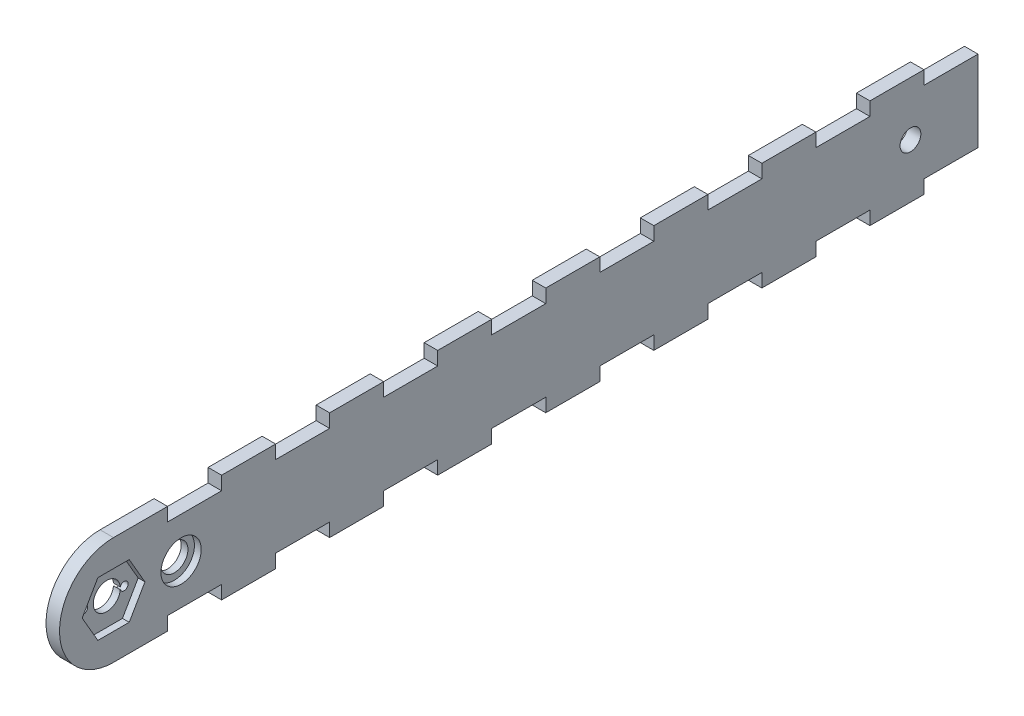
SolidWorks part; units mm, degrees
ref_plane "Front Plane" through (0, 0, 0) normal (0, 0, 1) x (1, 0, 0)
ref_plane "Top Plane" through (0, 0, 0) normal (0, 1, 0) x (1, 0, 0)
ref_plane "Right Plane" through (0, 0, 0) normal (1, 0, 0) x (0, 0, -1)
sketch "Sketch1" plane through (0, 0, 0) normal (1, 0, 0) x (0, 0, -1)
  line L0 (0, 12.7) -> (203.2, 12.7)
  line L1 (0, -12.7) -> (203.2, -12.7)
  line L2 (203.2, -12.7) -> (203.2, 12.7)
  line L3 (203.2, 0) -> (7.9375, 0) construction
  line L4 (203.2, 12.7) -> (190.5, 12.7)
  line L5 (203.2, 12.7) -> (203.2, 9.525)
  line L6 (203.2, 9.525) -> (190.5, 9.525)
  line L7 (190.5, 12.7) -> (190.5, 9.525)
  line L8 (190.5, -12.7) -> (190.5, -9.525)
  line L9 (203.2, -9.525) -> (190.5, -9.525)
  line L10 (203.2, -12.7) -> (203.2, -9.525)
  line L11 (165.1, 12.7) -> (165.1, 9.525)
  line L12 (165.1, -12.7) -> (165.1, -9.525)
  line L13 (177.8, -9.525) -> (165.1, -9.525)
  line L14 (177.8, 9.525) -> (165.1, 9.525)
  line L15 (177.8, 12.7) -> (177.8, 9.525)
  line L16 (177.8, -12.7) -> (177.8, -9.525)
  line L17 (139.7, 12.7) -> (139.7, 9.525)
  line L18 (139.7, -12.7) -> (139.7, -9.525)
  line L19 (152.4, -9.525) -> (139.7, -9.525)
  line L20 (152.4, 9.525) -> (139.7, 9.525)
  line L21 (152.4, 12.7) -> (152.4, 9.525)
  line L22 (152.4, -12.7) -> (152.4, -9.525)
  line L23 (114.3, 12.7) -> (114.3, 9.525)
  line L24 (114.3, -12.7) -> (114.3, -9.525)
  line L25 (127, -9.525) -> (114.3, -9.525)
  line L26 (127, 9.525) -> (114.3, 9.525)
  line L27 (127, 12.7) -> (127, 9.525)
  line L28 (127, -12.7) -> (127, -9.525)
  line L29 (88.9, 12.7) -> (88.9, 9.525)
  line L30 (88.9, -12.7) -> (88.9, -9.525)
  line L31 (101.6, -9.525) -> (88.9, -9.525)
  line L32 (101.6, 9.525) -> (88.9, 9.525)
  line L33 (101.6, 12.7) -> (101.6, 9.525)
  line L34 (101.6, -12.7) -> (101.6, -9.525)
  line L35 (63.5, 12.7) -> (63.5, 9.525)
  line L36 (63.5, -12.7) -> (63.5, -9.525)
  line L37 (76.2, -9.525) -> (63.5, -9.525)
  line L38 (76.2, 9.525) -> (63.5, 9.525)
  line L39 (76.2, 12.7) -> (76.2, 9.525)
  line L40 (76.2, -12.7) -> (76.2, -9.525)
  line L41 (38.1, 12.7) -> (38.1, 9.525)
  line L42 (38.1, -12.7) -> (38.1, -9.525)
  line L43 (50.8, -9.525) -> (38.1, -9.525)
  line L44 (50.8, 9.525) -> (38.1, 9.525)
  line L45 (50.8, 12.7) -> (50.8, 9.525)
  line L46 (50.8, -12.7) -> (50.8, -9.525)
  line L47 (12.7, 12.7) -> (12.7, 9.525)
  line L48 (12.7, -12.7) -> (12.7, -9.525)
  line L49 (25.4, -9.525) -> (12.7, -9.525)
  line L50 (25.4, 9.525) -> (12.7, 9.525)
  line L51 (25.4, 12.7) -> (25.4, 9.525)
  line L52 (25.4, -12.7) -> (25.4, -9.525)
  circle A0 centre (0, 0) radius 3.175
  arc A1 (0, 12.7) -> (0, -12.7) centre (0, 0) ccw
  dimension "D1" = 6.35
  dimension "D2" = 25.4
  dimension "D3" = 203.2
  dimension "D4" = 3.175
  dimension "D5" = 12.7
  dimension "D7" = 12.7
  dimension "D6" = 8
extrude "Boss-Extrude1" add sketch "Sketch1" along normal blind 3.175
sketch "Sketch2" plane through (3.175, 0, 0) normal (1, 0, 0) x (0, 0, -1)
  line L0 (15.875, 0) -> (0, 0) construction
  line L1 (203.2, 0) -> (187.325, 0) construction
  line L2 (203.2, -9.525) -> (203.2, 9.525) construction
  circle A0 centre (0, 0) radius 7.9375 construction
  circle A1 centre (15.875, 0) radius 7.9375 construction
  circle A2 centre (15.875, 0) radius 3.2004
  circle A5 centre (187.325, 0) radius 2.4384
  dimension "D1" = 15.875
  dimension "D2" = 6.4008
  dimension "D4" = 4.8768
  dimension "D3" = 15.875
extrude "Cut-Extrude2" cut sketch "Sketch2" against normal through all
sketch "Sketch3" plane through (3.175, 0, 0) normal (1, 0, 0) x (0, 0, -1)
  line L0 (0, 0) -> (0, 6.3881) construction
  line L1 (3.6882, -6.3881) -> (7.3763, 0)
  line L2 (7.3763, 0) -> (3.6882, 6.3881)
  line L3 (3.6882, 6.3881) -> (-3.6882, 6.3881)
  line L4 (-3.6882, 6.3881) -> (-7.3763, 0)
  line L5 (-7.3763, 0) -> (-3.6882, -6.3881)
  line L6 (-3.6882, -6.3881) -> (3.6882, -6.3881)
  line L7 (12.7, 12.7) -> (12.7, 9.525) construction
  circle A0 centre (0, 0) radius 6.3881 construction
  circle A1 centre (15.875, 0) radius 4.7307
  circle A2 centre (15.875, 0) radius 3.2004 construction
  dimension "D2" = 9.4615
  dimension "D1" = 12.7762
extrude "Cut-Extrude3" cut sketch "Sketch3" against normal blind 1.5875
sketch "Sketch5" plane through (3.175, 0, 0) normal (1, 0, 0) x (0, 0, -1)
  line L0 (-0.6881, 0) -> (-10.2131, 0) construction
  line L1 (-0.6881, 0) -> (8.8369, 0) construction
  circle A0 centre (-5.4506, 0) radius 0.9525
  circle A1 centre (4.0744, 0) radius 0.9525
  dimension "D1" = 1.905
  dimension "D3" = 1.905
  dimension "D2" = 4.7625
  dimension "D4" = 4.7625
extrude "Cut-Extrude4" cut sketch "Sketch5" against normal through all
